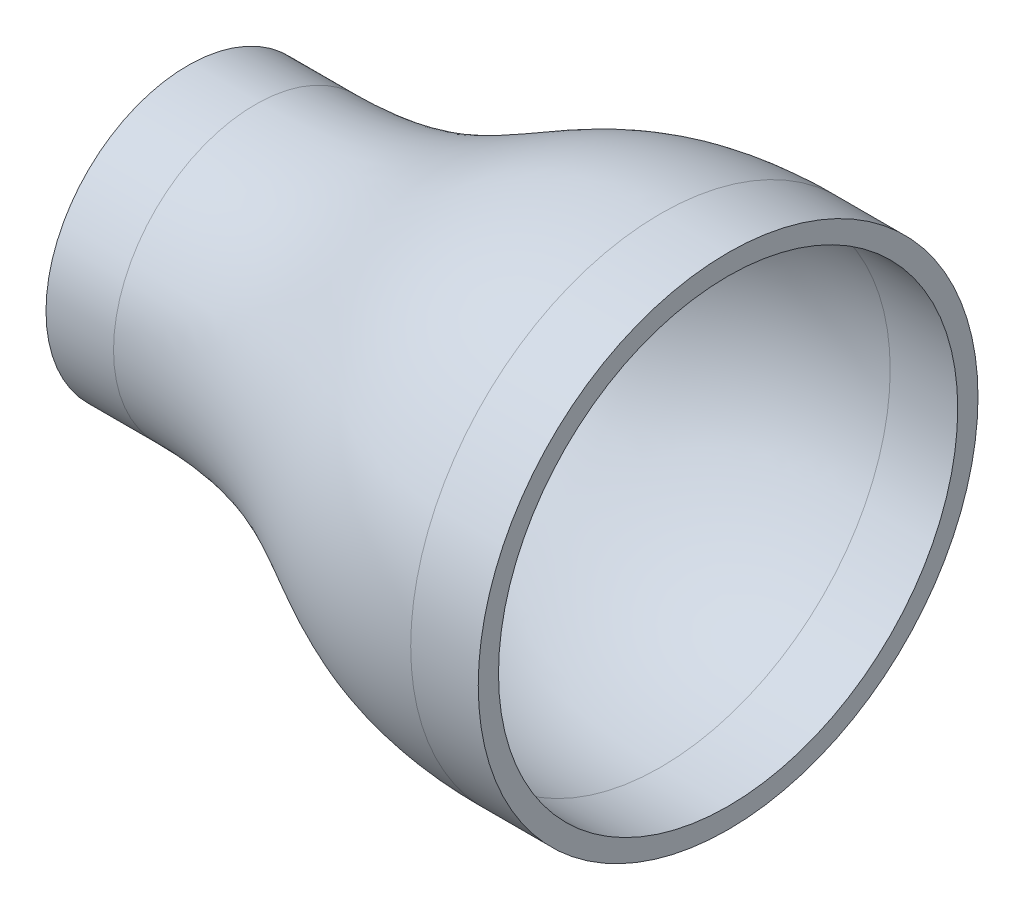
SolidWorks part; units mm, degrees
ref_plane "Front" through (0, 0, 0) normal (0, 0, 1) x (1, 0, 0)
ref_plane "Top" through (0, 0, 0) normal (0, 1, 0) x (1, 0, 0)
ref_plane "Right" through (0, 0, 0) normal (1, 0, 0) x (0, 0, -1)
sketch "Sketch1" plane through (0, 0, 0) normal (0, 1, 0) x (1, 0, 0)
  line L0 (0, 0) -> (30, 0) construction
  line L1 (0, 10.5) -> (0, 9) construction
  line L2 (0, 9) -> (15, 9) construction
  line L3 (30, 17) -> (30, 18.5) construction
  line L4 (15, 9) -> (15, 17) construction
  line L5 (15, 17) -> (30, 17) construction
  line L6 (30, 17) -> (30, 0) construction
  line L7 (0, 9) -> (0, 0) construction
  line L8 (0, 9) -> (-5, 9)
  line L9 (-5, 9) -> (-5, 10.5)
  line L10 (-5, 10.5) -> (0, 10.5)
  line L11 (30, 17) -> (35, 17)
  line L12 (35, 17) -> (35, 18.5)
  line L13 (35, 18.5) -> (30, 18.5)
  line L14 (0, 10.5) -> (15, 10.5) construction
  line L15 (15, 10.5) -> (15, 18.5) construction
  line L16 (15, 18.5) -> (30, 18.5) construction
  spline S0 degree 3 poles (0, 9) (15, 9) (15, 17) (30, 17) knots 0 0 0 0 1 1 1 1
  spline S1 degree 3 poles (0, 10.5) (15, 10.5) (15, 18.5) (30, 18.5) knots 0 0 0 0 1 1 1 1
  dimension "D1" = 1.5
  dimension "D2" = 30
  dimension "D3" = 18
  dimension "D4" = 34
  dimension "D5" = 5
  dimension "D6" = 2
revolve "Revolve1" add sketch "Sketch1" angle 360 about L0
